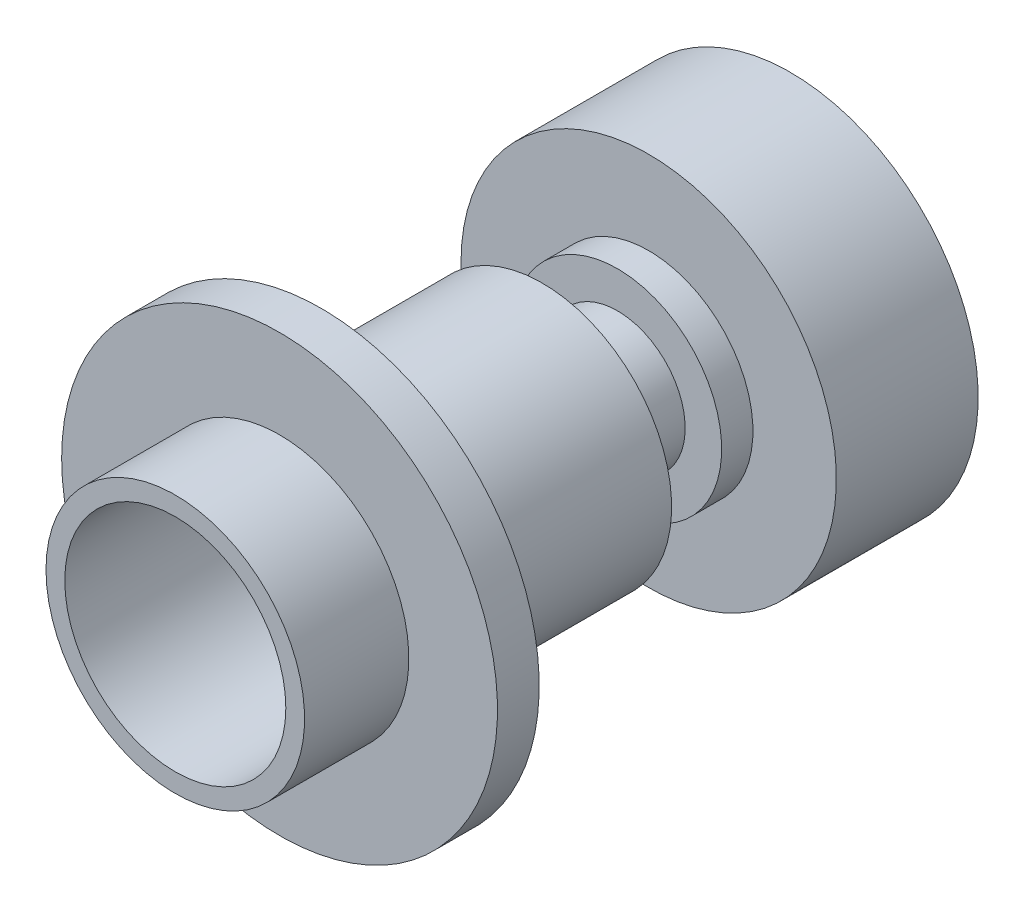
SolidWorks part; units mm, degrees
ref_plane "Top" through (0, 0, 0) normal (0, 0, 1) x (1, 0, 0)
ref_plane "Front" through (0, 0, 0) normal (0, 1, 0) x (1, 0, 0)
ref_plane "Right" through (0, 0, 0) normal (1, 0, 0) x (0, 0, -1)
sketch "Body Sketch" plane through (0, 0, 0) normal (0, 1, 0) x (1, 0, 0)
  line L0 (0, 0) -> (0, -14.75) construction
  line L2 (2.65, -14.75) -> (3.1, -14.75)
  line L3 (3.1, -14.75) -> (3.1, -12.25)
  line L4 (3.1, -12.25) -> (5.225, -12.25)
  line L5 (5.225, -12.25) -> (5.225, -11.25)
  line L6 (5.225, -11.25) -> (3.1, -11.25)
  line L7 (3.1, -11.25) -> (3.1, -5.95)
  line L8 (3.1, -5.95) -> (1.625, -5.55)
  line L9 (1.625, -5.55) -> (1.625, -4.15)
  line L10 (1.625, -4.15) -> (2.5, -4.15)
  line L11 (2.5, -4.15) -> (2.5, -3.4)
  line L12 (2.5, -3.4) -> (0.25, -3.4)
  line L17 (0.25, -3.4) -> (0.25, -5.9542)
  line L18 (0.25, -5.9542) -> (2.65, -6.6051)
  line L19 (2.65, -6.6051) -> (2.65, -14.75)
  dimension "D1" = 0.25
  dimension "D3" = 2.5
  dimension "D4" = 0.75
  dimension "D10" = 1.625
  dimension "D11" = 1.4
  dimension "D12" = 0.4
  dimension "D13" = 3.1
  dimension "D14" = 5.225
  dimension "D15" = 1
  dimension "D16" = 2.5
  dimension "D17" = 2.65
  dimension "D18" = 0.75
  dimension "Tip Length" = 3.4
  dimension "D2" = 11.35
revolve "Body Revolve" add sketch "Body Sketch" angle 360 about L0
sketch "N045 Sketch" plane through (0, 0, 0) normal (0, 1, 0) x (1, 0, 0)
  line L0 (0, 0) -> (0, -3.4) construction
  line L4 (1.25, -3.4) -> (0.25, -3.4)
  line L5 (1.25, -3.4) -> (1, -0.75)
  line L6 (1, -0.75) -> (0.78, -0.75)
  line L7 (0.78, -0.75) -> (0.78, 0)
  line L8 (0.78, 0) -> (0.25, 0)
  line L9 (0.25, 0) -> (0.25, -3.4)
  point P2 (0.515, 0)
  dimension "D1" = 1.25
  dimension "D2" = 0.75
  dimension "D4" = 0.25
  dimension "D5" = 0.78
  dimension "D6" = 1
  dimension "Tip Length" = 3.4
revolve "N045 Revolve" [suppressed] add sketch "N045 Sketch" angle 360 about L0
sketch "N08 Sketch" [suppressed] plane through (0, 0, 0) normal (0, 1, 0) x (1, 0, 0)
  line L0 (0.5, 0) -> (0.75, 0)
  line L1 (0.75, 0) -> (0.75, -0.75)
  line L2 (0.75, -0.75) -> (1.25, -3.4)
  line L3 (1.25, -3.4) -> (0.5, -3.4)
  line L4 (0.5, -3.4) -> (0.5, 0)
  line L5 (0, 0) -> (0, -3.4) construction
  dimension "D1" = 3.4
  dimension "D2" = 0.75
  dimension "D3" = 0.5
  dimension "D4" = 0.75
  dimension "D5" = 1.25
revolve "N08 Revolve" [suppressed] add sketch "N08 Sketch" angle 360 about L5
sketch "N14 Sketch" plane through (0, 0, 0) normal (0, 1, 0) x (1, 0, 0)
  line L0 (0.7, 0) -> (1.125, 0)
  line L1 (1.125, 0) -> (1.125, -2.25)
  line L2 (1.125, -2.25) -> (1.25, -3.4)
  line L3 (1.25, -3.4) -> (0.7, -3.4)
  line L4 (0.7, -3.4) -> (0.7, 0)
  line L5 (0, 0) -> (0, -3.4) construction
  dimension "D1" = 0.7
  dimension "D2" = 1.125
  dimension "D3" = 1.25
  dimension "D4" = 2.25
  dimension "Tip Length" = 3.4
revolve "N14 Revolve" [suppressed] add sketch "N14 Sketch" angle 360 about L5
sketch "N24 Sketch" plane through (0, 0, 0) normal (0, 1, 0) x (1, 0, 0)
  line L0 (1.2, 0) -> (2, 0)
  line L1 (2, 0) -> (2, -3.4)
  line L3 (2, -3.4) -> (1.2, -3.4)
  line L4 (1.2, -3.4) -> (1.2, 0)
  line L5 (0, 0) -> (0, -3.4) construction
  dimension "D3" = 1.2
  dimension "D4" = 2
  dimension "Tip Length" = 3.4
revolve "N24 Revolve" [suppressed] add sketch "N24 Sketch" angle 360 about L5
sketch "N40 Sketch" [suppressed] plane through (0, 0, 0) normal (0, 1, 0) x (1, 0, 0)
  line L0 (2, 0) -> (3.1, 0)
  line L1 (3.1, 0) -> (3.1, -3.4)
  line L3 (3.1, -3.4) -> (2, -3.4)
  line L4 (2, -3.4) -> (2, 0)
  line L5 (0, 0) -> (0, -3.4) construction
  dimension "D1" = 3.4
  dimension "D3" = 2
  dimension "D4" = 3.1
revolve "N40 Revolve" [suppressed] add sketch "N40 Sketch" angle 360 about L5
sketch "N75 Sketch" plane through (0, 0, 0) normal (0, 1, 0) x (1, 0, 0)
  line L0 (3.75, 0) -> (4.5, 0)
  line L1 (4.5, 0) -> (4.5, -3.4)
  line L3 (4.5, -3.4) -> (0.8, -3.4)
  line L4 (3.75, -2.65) -> (3.75, 0)
  line L5 (0, 0) -> (0, -3.4) construction
  line L6 (0.8, -2.65) -> (3.75, -2.65)
  line L7 (0.8, -2.65) -> (0.8, -3.4)
  dimension "D1" = 3.4
  dimension "D2" = 0.8
  dimension "D3" = 3.75
  dimension "D4" = 4.5
  dimension "D5" = 0.75
revolve "N75 Revolve" add sketch "N75 Sketch" angle 360 about L5
equation "\"D10@Body Sketch\" = 3.25 / 2"
